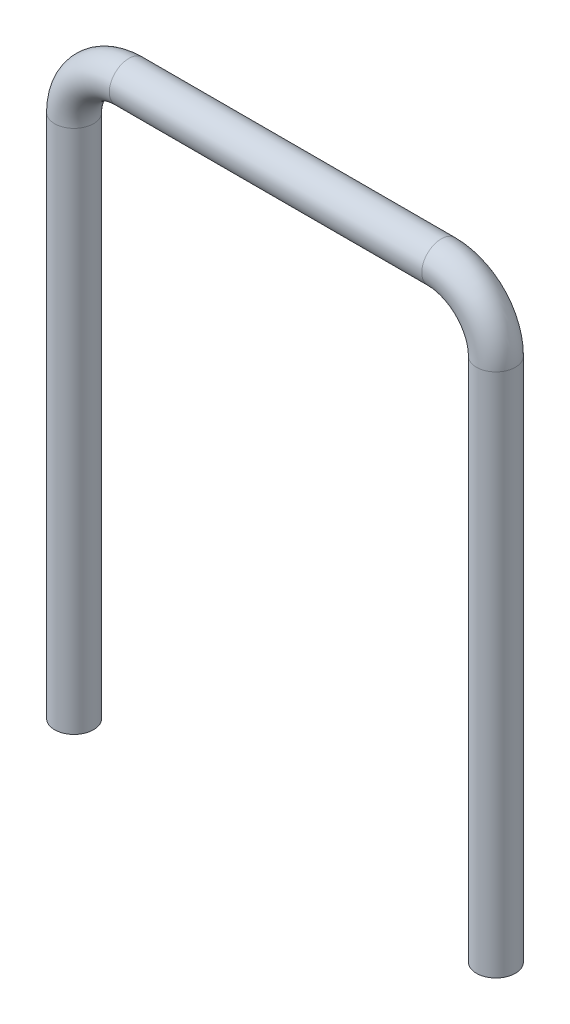
SolidWorks part; units mm, degrees
ref_plane "Front Plane" through (0, 0, 0) normal (0, 0, 1) x (1, 0, 0)
ref_plane "Top Plane" through (0, 0, 0) normal (0, 1, 0) x (1, 0, 0)
ref_plane "Right Plane" through (0, 0, 0) normal (1, 0, 0) x (0, 0, -1)
sketch "Sketch1" plane through (0, 0, 0) normal (0, 1, 0) x (1, 0, 0)
  circle A0 centre (0, 0) radius 0.3556
  dimension "D1" = 0.7112
sketch "Sketch2" plane through (0, 0, 0) normal (0, 0, 1) x (1, 0, 0)
  line L0 (0, 0) -> (0, 10.5944) construction
  line L1 (0, 10.5944) -> (7.7112, 10.5944) construction
  line L2 (7.7112, 10.5944) -> (7.7112, 7.6755) construction
  line L3 (0, 9.5944) -> (0, 0)
  line L4 (3.8556, 10.5944) -> (3.8556, 11.6677) construction
  line L5 (7.7112, 9.5944) -> (7.7112, 0)
  line L6 (1, 10.5944) -> (6.7112, 10.5944)
  line L7 (7.3556, 9.5944) -> (7.3556, 0) construction
  line L8 (1, 10.2388) -> (6.7112, 10.2388) construction
  line L9 (0.3556, 9.5944) -> (0.3556, 0) construction
  line L10 (-0.3556, 9.5944) -> (-0.3556, 0) construction
  line L11 (1, 10.95) -> (6.7112, 10.95) construction
  line L12 (8.0668, 9.5944) -> (8.0668, 0) construction
  line L13 (0.3556, 0) -> (-0.3556, 0) construction
  arc A0 (0, 9.5944) -> (1, 10.5944) centre (1, 9.5944) cw
  arc A1 (7.3556, 9.5944) -> (6.7112, 10.2388) centre (6.7112, 9.5944) ccw construction
  arc A2 (7.7112, 9.5944) -> (6.7112, 10.5944) centre (6.7112, 9.5944) ccw
  arc A3 (0.3556, 9.5944) -> (1, 10.2388) centre (1, 9.5944) cw construction
  arc A4 (-0.3556, 9.5944) -> (1, 10.95) centre (1, 9.5944) cw construction
  arc A5 (8.0668, 9.5944) -> (6.7112, 10.95) centre (6.7112, 9.5944) ccw construction
  point P11 (0.5, 10.0944)
  point P17 (7.1885, 0)
  point P19 (5.2683, 0)
  point P20 (4.655, 10.5944)
  dimension "D1" = 1
  dimension "D2" = 10.95
  dimension "D3" = 0.3556
  dimension "D4" = 7
  dimension "D6" = 8.4224
  dimension "D5" = 0.3556
sweep "Sweep1" add profiles "Sketch1" path "Sketch2"
